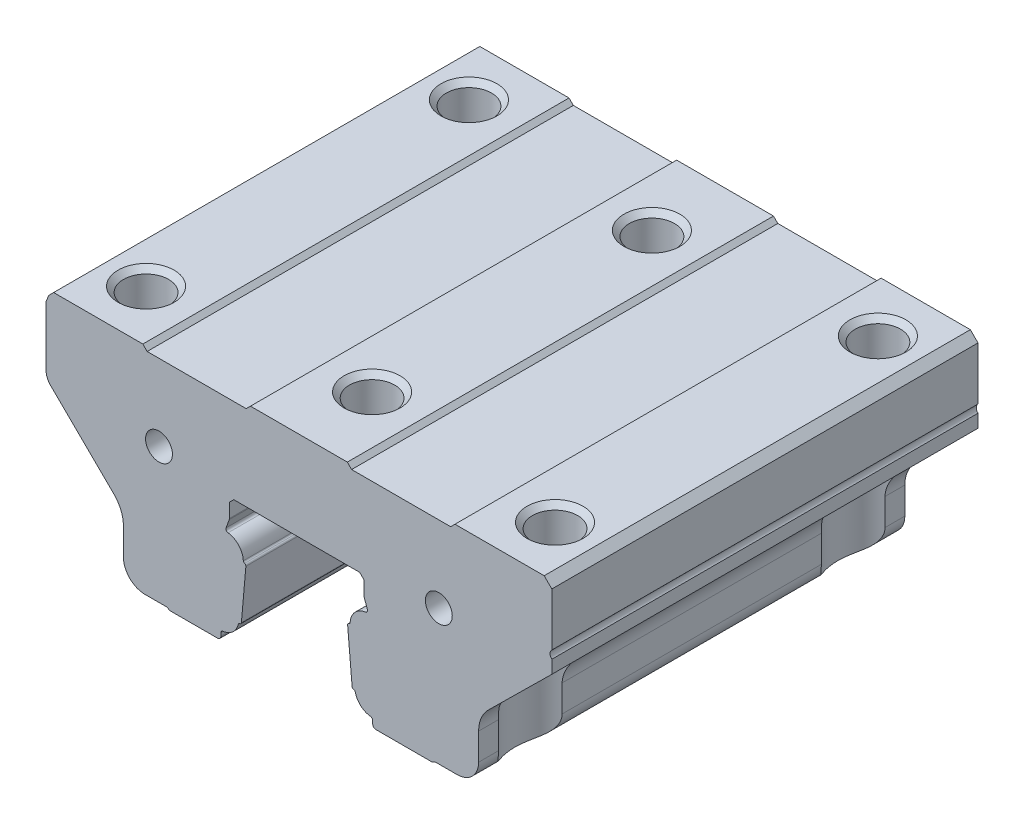
SolidWorks part; units mm, degrees
ref_plane "Front Plane" through (0, 0, 0) normal (0, 0, 1) x (1, 0, 0)
ref_plane "Top Plane" through (0, 0, 0) normal (0, 1, 0) x (1, 0, 0)
ref_plane "Right Plane" through (0, 0, 0) normal (1, 0, 0) x (0, 0, -1)
sketch "Sketch2" plane through (0, 0, 0) normal (0, 0, -1) x (-1, 0, 0)
  line L0 (0, 0) -> (0, 16.4265) construction
  line L1 (0, 0) -> (0, -12.0517) construction
  line L13 (23.2405, 9.65) -> (22.7905, 10.1)
  line L14 (22.7905, 10.1) -> (14.5005, 10.1)
  line L15 (14.5005, 10.1) -> (14.1005, 9.7)
  line L16 (14.1005, 9.7) -> (5.8845, 9.7)
  line L17 (5.8845, 9.7) -> (4.9005, 9.7)
  line L18 (4.9005, 9.7) -> (4.5005, 10.1)
  line L19 (4.5005, 10.1) -> (-4.4995, 10.1)
  line L20 (-4.4995, 10.1) -> (-4.8995, 9.7)
  line L21 (-4.8995, 9.7) -> (-5.8845, 9.7)
  line L22 (-5.8845, 9.7) -> (-14.0995, 9.7)
  line L23 (-14.0995, 9.7) -> (-14.4995, 10.1)
  line L24 (-14.4995, 10.1) -> (-22.7895, 10.1)
  line L25 (-22.7895, 10.1) -> (-23.2395, 9.65)
  line L58 (7.2576, -9.5204) -> (7.2576, -10.1)
  line L59 (7.2576, -10.1) -> (12.0241, -10.1)
  line L60 (12.3811, -9.95) -> (14.3061, -9.95)
  line L61 (16.3061, -7.95) -> (16.3061, -5.4426)
  line L62 (17.1848, -3.3213) -> (23.0607, 2.4607)
  line L63 (23.5, 3.5213) -> (23.5, 8.9961)
  line L64 (23.5, 8.9961) -> (23.2405, 9.65)
  line L70 (-23.2395, 9.65) -> (-23.5, 9.3895)
  line L71 (-23.5, 9.3895) -> (-23.5, 4.4729)
  line L72 (-23.5, 3.7351) -> (-23.5, 2.5217)
  line L73 (-23.5, 2.5217) -> (-17.5782, -3.3213)
  line L74 (-16.6995, -5.4486) -> (-16.6995, -7.95)
  line L75 (-14.6995, -9.95) -> (-12.7745, -9.95)
  line L76 (-12.4174, -10.1) -> (-6.8566, -10.1)
  line L77 (-6.8566, -10.1) -> (-6.8566, -9.5204)
  line L78 (-4.9426, -7.7418) -> (-4.5278, -3.0009)
  line L79 (-6.3654, -0.8255) -> (-6.0676, -0.0072)
  line L80 (-6.0495, 0.0954) -> (-6.0495, 1.4)
  line L81 (-6.0495, 1.4) -> (-5.6495, 1.8)
  line L82 (-5.6495, 1.8) -> (6.0505, 1.8)
  line L83 (6.0505, 1.8) -> (6.4505, 1.4)
  line L84 (6.4505, 1.4) -> (6.4505, 0.0954)
  line L85 (6.4686, -0.0072) -> (6.7664, -0.8255)
  line L86 (4.9288, -3.0009) -> (5.3436, -7.7418)
  arc A4 (-12.1972, 2.6) -> (-14.1972, 2.6) centre (-13.1972, 2.6) ccw construction
  arc A5 (-14.1972, 2.6) -> (-12.1972, 2.6) centre (-13.1972, 2.6) ccw construction
  arc A6 (13.8028, 2.6) -> (11.8028, 2.6) centre (12.8028, 2.6) ccw construction
  arc A7 (11.8028, 2.6) -> (13.8028, 2.6) centre (12.8028, 2.6) ccw construction
  arc A58 (12.3811, -9.95) -> (12.0241, -10.1) centre (12.3811, -10.45) ccw
  arc A59 (14.3061, -9.95) -> (16.3061, -7.95) centre (14.3061, -7.95) ccw
  arc A60 (17.1848, -3.3213) -> (16.3061, -5.4426) centre (19.3061, -5.4426) ccw
  arc A61 (23.0607, 2.4607) -> (23.5, 3.5213) centre (22, 3.5213) ccw
  arc A62 (-23.3375, 4.104) -> (-23.5, 4.4729) centre (-23.8375, 4.104) ccw
  arc A63 (-23.5, 3.7351) -> (-23.3375, 4.104) centre (-23.8375, 4.104) ccw
  arc A64 (-16.6995, -5.4486) -> (-17.5782, -3.3213) centre (-19.7138, -5.4486) ccw
  arc A65 (-16.6995, -7.95) -> (-14.6995, -9.95) centre (-14.6995, -7.95) ccw
  arc A66 (-12.4174, -10.1) -> (-12.7745, -9.95) centre (-12.7745, -10.45) ccw
  arc A67 (-6.6533, -9.2929) -> (-6.8566, -9.5204) centre (-6.6276, -9.5204) ccw
  arc A68 (-6.6533, -9.2929) -> (-5.2376, -8.0281) centre (-6.8373, -7.6622) ccw
  arc A69 (-5.0919, -7.8966) -> (-5.2376, -8.0281) centre (-5.0709, -8.0663) ccw
  arc A70 (-5.0919, -7.8966) -> (-4.9426, -7.7418) centre (-5.1129, -7.7269) ccw
  arc A71 (-4.5278, -3.0009) -> (-4.5272, -2.986) centre (-4.6982, -2.986) ccw
  arc A72 (-4.5272, -2.986) -> (-4.6451, -2.8234) centre (-4.6982, -2.986) ccw
  arc A73 (-4.7628, -2.6699) -> (-4.6451, -2.8234) centre (-4.5921, -2.6609) ccw
  arc A74 (-4.7628, -2.6699) -> (-6.181, -1.1308) centre (-6.4015, -2.7569) ccw
  arc A75 (-6.3654, -0.8255) -> (-6.181, -1.1308) centre (-6.1502, -0.9039) ccw
  arc A76 (-6.0676, -0.0072) -> (-6.0495, 0.0954) centre (-6.3495, 0.0954) ccw
  arc A77 (6.4505, 0.0954) -> (6.4686, -0.0072) centre (6.7505, 0.0954) ccw
  arc A78 (6.7803, -0.9039) -> (6.7664, -0.8255) centre (6.5513, -0.9039) ccw
  arc A79 (6.582, -1.1308) -> (6.7803, -0.9039) centre (6.5513, -0.9039) ccw
  arc A80 (6.582, -1.1308) -> (5.1639, -2.6699) centre (6.8026, -2.7569) ccw
  arc A81 (5.0461, -2.8234) -> (5.1639, -2.6699) centre (4.9931, -2.6609) ccw
  arc A82 (5.0461, -2.8234) -> (4.9288, -3.0009) centre (5.0992, -2.986) ccw
  arc A83 (5.3436, -7.7418) -> (5.493, -7.8966) centre (5.5139, -7.7269) ccw
  arc A84 (5.6387, -8.0281) -> (5.493, -7.8966) centre (5.472, -8.0663) ccw
  arc A85 (5.6387, -8.0281) -> (7.0543, -9.2929) centre (7.2383, -7.6622) ccw
  arc A86 (7.2576, -9.5204) -> (7.0543, -9.2929) centre (7.0286, -9.5204) ccw
  dimension "D1" = 47
extrude "Extrude1" add sketch "Sketch2" along normal mid plane 39.6
ref_plane "Plane1" through (0, 0, 15) normal (0, 0, 1) x (1, 0, 0)
sketch "Sketch3" plane through (0, 0, 15) normal (0, 0, 1) x (1, 0, 0)
  line L0 (0, 0) -> (0, 18.3827) construction
  line L1 (0, 0) -> (0, -17.442) construction
  line L2 (-19, 22.6869) -> (-19, -20.9861) construction
  line L3 (-22.7905, 10.1) -> (-14.5005, 10.1) construction
  line L4 (-22.7905, 10.1) -> (-14.5005, 10.1) construction
  line L5 (-21.1, 10.1) -> (-21.1, 3.1)
  line L6 (-21.1, 3.1) -> (-22.75, 3.1)
  line L7 (-22.75, 3.1) -> (-22.75, -10.1)
  line L8 (-22.75, -10.1) -> (-19, -10.1)
  line L9 (-19, -10.1) -> (-19, 10.1)
  line L10 (-19, 10.1) -> (-21.1, 10.1)
  line L11 (-7.2576, -10.1) -> (-12.0241, -10.1) construction
  dimension "D1" = 19
  dimension "D2" = 4.2
  dimension "D3" = 7.5
  dimension "D4" = 7
revolve "Cut-Revolve1" cut sketch "Sketch3" angle 360 about L2
pattern_linear "LPattern1" count 2 spacing 30 along (0, 0, -1) count 2 spacing 38 along (1, 0, 0) of "Cut-Revolve1"
ref_plane "Plane2" through (0, 0, 13) normal (0, 0, 1) x (1, 0, 0)
sketch "Sketch4" plane through (0, 0, 13) normal (0, 0, 1) x (1, 0, 0)
  line L0 (0, 0) -> (0, 19.8449) construction
  line L1 (-4.5005, 10.1) -> (4.4995, 10.1) construction
  line L2 (-4.5005, 10.1) -> (4.4995, 10.1) construction
  line L3 (-2.1, 10.1) -> (-2.1, 5.6)
  line L4 (-2.1, 5.6) -> (-3.75, 5.6)
  line L5 (-3.75, 5.6) -> (-3.75, 1.8)
  line L6 (5.6495, 1.8) -> (-6.0505, 1.8) construction
  line L7 (-3.75, 1.8) -> (0, 1.8)
  line L8 (0, 1.8) -> (0, 10.1)
  line L9 (-2.1, 10.1) -> (0, 10.1)
  dimension "D1" = 4.2
  dimension "D2" = 7.5
  dimension "D3" = 4.5
revolve "Cut-Revolve2" cut sketch "Sketch4" angle 360 about L0
pattern_linear "LPattern2" count 2 spacing 26 along (0, 0, -1) of "Cut-Revolve2"
hole_wizard "M2.5 Tapped Hole1" positions "3DSketch1" profile "Sketch6" tap size "M2.5" standard "ISO"
sketch3d "3DSketch1"
  line L0 (0, 0, 0) -> (0, 19.7721, 0) construction
  line L4 (0, 0, 0) -> (0, 26.2966, 0) construction
  point P0 (-13, 2.6, 19.8)
  point P2 (13, 2.6, 19.8)
  dimension "D1" = 12.7
  dimension "D2" = 13
  dimension "D3" = 26
sketch "Sketch6" plane through (-13, 2.6, 19.8) normal (1, 0, 0) x (0, -1, 0)
  line L0 (0, 0) -> (0, 6.9659)
  line L1 (0, 6.9659) -> (1.025, 6.35)
  line L2 (1.025, 6.35) -> (1.025, 5)
  line L3 (1.025, 5) -> (1.25, 5)
  line L4 (1.25, 5) -> (1.25, 0)
  line L5 (1.25, 0) -> (0, 0)
  line L10 (0, 6.9659) -> (-1.025, 6.35) construction
  line L11 (0, -6.35) -> (0, 107.95) construction
  dimension "Tap Drill Dia." = 2.05
  dimension "Tap Drill Depth" = 6.35
  dimension "Thread Major Dia." = 2.5
  dimension "Thread Depth" = 5
  dimension "Drill Angle" = 118
mirror "Mirror1" about plane through (0, 0, 0) normal (0, 0, 1) of "M2.5 Tapped Hole1"
chamfer "Chamfer1" distance 0.5 angle 45 6 edges at (-21.1, 10.1, 15) (-21.1, 10.1, -15) (0, 10.1, -15.1) (16.9, 10.1, -15) (0, 10.1, 10.9) (16.9, 10.1, 15)
fillet "Fillet1" radius 0.3 2 edges at (-7.2576, -10.1, 0) (6.8566, -10.1, 0)
sketch "Sketch7" plane through (0, 10.1, 0) normal (0, 1, 0) x (1, 0, 0)
  line L0 (0, 0) -> (-0.0005, 19.8) construction
  line L1 (-19, 15) -> (-19, -15) construction
  line L2 (-4.5005, 19.8) -> (4.4995, 19.8) construction
  circle A0 centre (-19, 0) radius 3
  dimension "D2" = 6
  dimension "D1" = 15
extrude "Cut-Extrude1" [suppressed] cut sketch "Sketch7" against normal blind 7
mirror "Mirror2" [suppressed] about plane through (0, 0, 0) normal (1, 0, 0)
